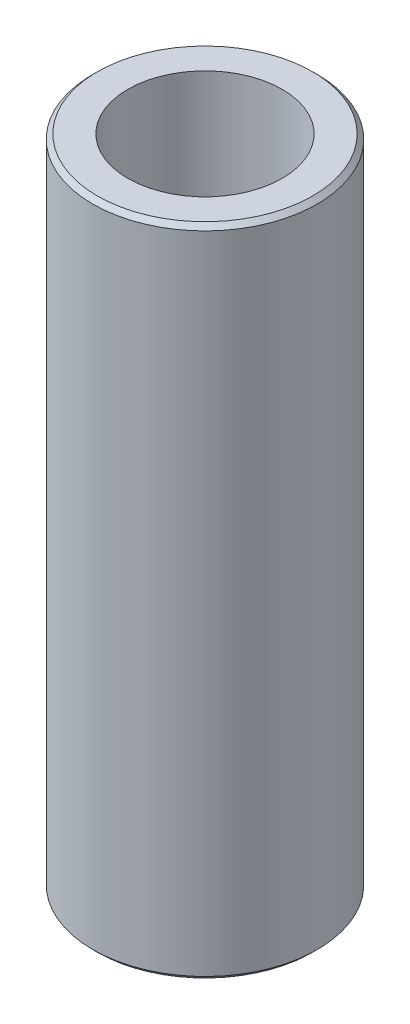
SolidWorks part; units mm, degrees
ref_plane "Ön Düzlem" through (0, 0, 0) normal (0, 0, 1) x (1, 0, 0)
ref_plane "Üst Düzlem" through (0, 0, 0) normal (0, 1, 0) x (1, 0, 0)
ref_plane "Sağ Düzlem" through (0, 0, 0) normal (1, 0, 0) x (0, 0, -1)
sketch "Çizim1" plane through (0, 0, 0) normal (0, 1, 0) x (1, 0, 0)
  circle A0 centre (0, 0) radius 2.4
  circle A1 centre (0, 0) radius 1.65
  dimension "D1" = 4.8
  dimension "D2" = 3.3
extrude "Yükseklik-Ekstrüzyon1" add sketch "Çizim1" along normal blind 14
chamfer "Pah1" distance 0.1 angle 45 2 edges at (0, 0, 2.4) (0, 14, 2.4)
